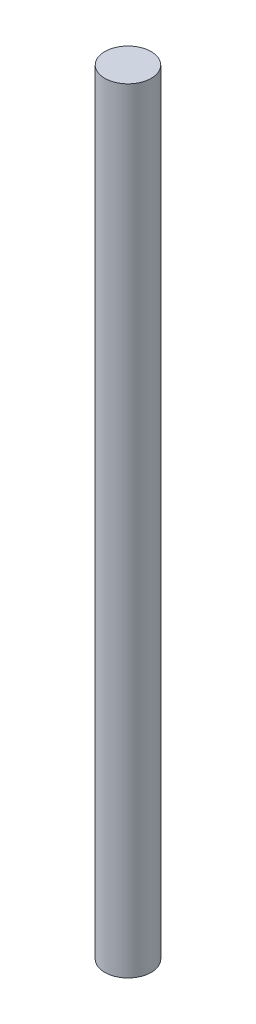
SolidWorks part; units mm, degrees
ref_plane "前视基准面" through (0, 0, 0) normal (0, 0, 1) x (1, 0, 0)
ref_plane "上视基准面" through (0, 0, 0) normal (0, 1, 0) x (1, 0, 0)
ref_plane "右视基准面" through (0, 0, 0) normal (1, 0, 0) x (0, 0, -1)
sketch "草图1" plane through (0, 0, 0) normal (0, 1, 0) x (1, 0, 0)
  circle A0 centre (0, 0) radius 1
  dimension "D1" = 2
extrude "凸台-拉伸1" add sketch "草图1" along normal blind 33.4
